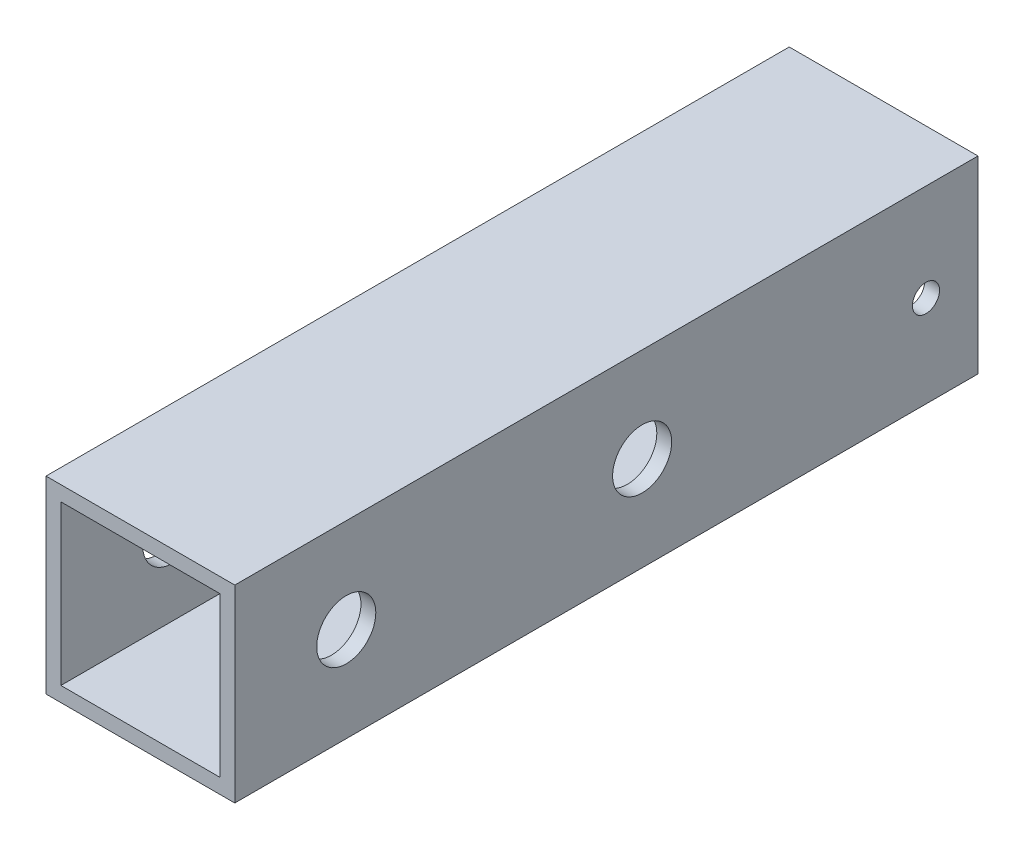
SolidWorks part; units mm, degrees
material "Acrylic (Medium-high impact)"
ref_plane "Front Plane" through (0, 0, 0) normal (0, 0, 1) x (1, 0, 0)
ref_plane "Top Plane" through (0, 0, 0) normal (0, 1, 0) x (1, 0, 0)
ref_plane "Right Plane" through (0, 0, 0) normal (1, 0, 0) x (0, 0, -1)
sketch "Sketch1" plane through (0, 0, 0) normal (0, 0, 1) x (1, 0, 0)
  line L1 (0, 0) -> (25.4, 0)
  line L2 (0, 0) -> (0, 25.4)
  line L3 (0, 25.4) -> (25.4, 25.4)
  line L4 (25.4, 0) -> (25.4, 25.4)
  line L5 (2, 23.4) -> (23.4, 23.4)
  line L6 (2, 23.4) -> (2, 2)
  line L7 (2, 2) -> (23.4, 2)
  line L8 (23.4, 23.4) -> (23.4, 2)
  dimension "D1" = 25.4
  dimension "D2" = 25.4
  dimension "D3" = 2
  dimension "D4" = 2
  dimension "D5" = 2
  dimension "D6" = 2
extrude "Boss-Extrude1" add sketch "Sketch1" along normal blind 100
sketch "Sketch2" plane through (25.4, 0, 0) normal (1, 0, 0) x (0, 0, -1)
  line L0 (0, 12.7) -> (-100, 12.7) construction
  line L1 (0, 0) -> (0, 25.4) construction
  line L2 (-100, 0) -> (-100, 25.4) construction
  circle A0 centre (-85, 12.7) radius 3.975
  circle A1 centre (-45.19, 12.7) radius 3.975
  dimension "D1" = 7.95
  dimension "D3" = 7.95
  dimension "D2" = 15
  dimension "D4" = 39.81
extrude "Cut-Extrude1" cut sketch "Sketch2" against normal blind 50
sketch "Sketch3" plane through (0, 0, 0) normal (0, -1, 0) x (1, 0, 0)
  line L0 (25.4, 100) -> (25.4, 0) construction
  line L1 (0, 0) -> (25.4, 0) construction
  line L2 (8.45, 70) -> (8.45, 10)
  line L3 (5.35, 10) -> (5.35, 70)
  circle A0 centre (6.9, 70) radius 1.55
  circle A1 centre (6.9, 10) radius 1.55
  dimension "D2" = 3.1
  dimension "D3" = 3.1
  dimension "D1" = 18.5
  dimension "D4" = 18.5
  dimension "D5" = 60
  dimension "D6" = 10
extrude "Cut-Extrude4" cut sketch "Sketch3" against normal blind 10
sketch "Sketch4" plane through (0, 0, 0) normal (0, -1, 0) x (1, 0, 0)
  line L0 (0, 0) -> (25.4, 0) construction
  circle A0 centre (7.5, 2.7657) radius 1.778
  circle A1 centre (17.5, 2.7657) radius 1.778
  dimension "D1" = 10
  dimension "D3" = 2.7657
  dimension "D2" = 2.7657
extrude "Cut-Extrude5" cut sketch "Sketch4" against normal blind 10
sketch "Sketch5" plane through (0, 0, 0) normal (-1, 0, 0) x (0, 0, 1)
  line L0 (0, 25.4) -> (0, 0) construction
  line L1 (0, 12.3239) -> (100, 12.7) construction
  line L2 (100, 25.4) -> (100, 0) construction
  circle A0 centre (7, 12.3502) radius 1.825
  dimension "D1" = 3.65
  dimension "D2" = 7
extrude "Cut-Extrude6" cut sketch "Sketch5" against normal up to surface (25.4 mm away) up to face at (25.4, 12.7, 41.215)
